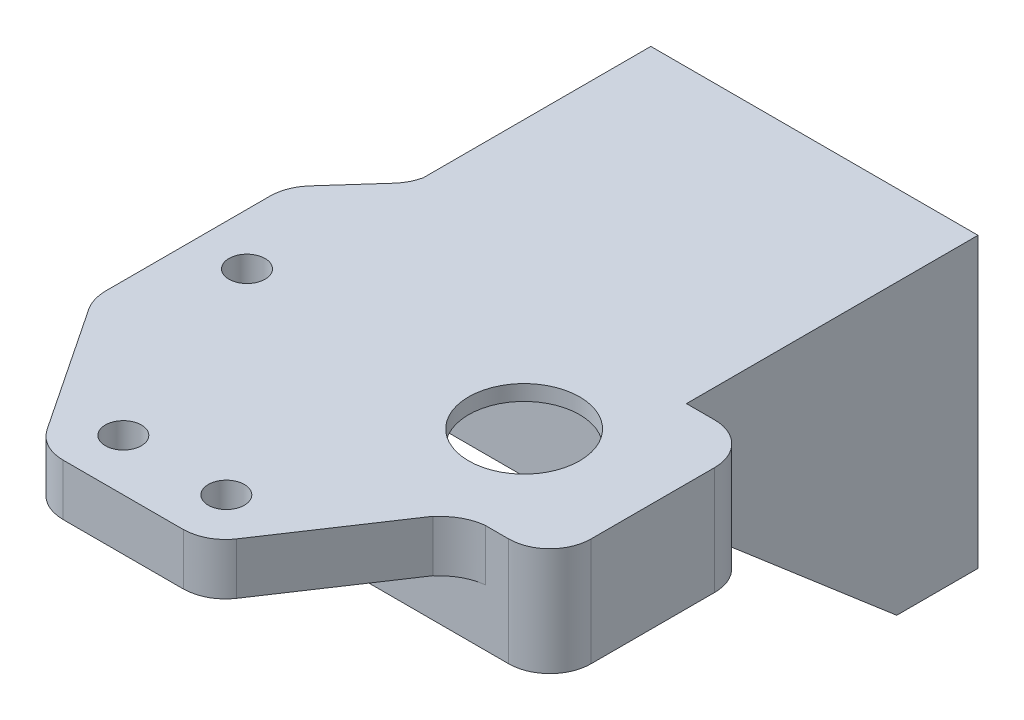
SolidWorks part; units mm, degrees
ref_plane "Alzado" through (0, 0, 0) normal (0, 0, 1) x (1, 0, 0)
ref_plane "Planta" through (0, 0, 0) normal (0, 1, 0) x (1, 0, 0)
ref_plane "Vista lateral" through (0, 0, 0) normal (1, 0, 0) x (0, 0, -1)
sketch "Croquis2" plane through (0, 0, 0) normal (0, 1, 0) x (1, 0, 0)
  line L0 (-15.9202, -3.4567) -> (19.0798, -3.4567)
  line L1 (19.0798, -3.4567) -> (19.0798, 16.5433)
  line L2 (19.0798, 16.5433) -> (-15.9202, 16.5433)
  line L3 (-15.9202, 16.5433) -> (-15.9202, -3.4567)
  dimension "D1" = 35
  dimension "D2" = 20
extrude "Saliente-Extruir1" add sketch "Croquis2" along normal blind 10.5
sketch "Croquis3" plane through (0, 0, 0) normal (0, -1, 0) x (1, 0, 0)
  line L0 (-9.9202, -0.0433) -> (-9.9202, -13.0433)
  line L1 (-9.9202, -13.0433) -> (13.0798, -13.0433)
  line L2 (13.0798, -13.0433) -> (13.0798, -0.0433)
  line L3 (13.0798, -0.0433) -> (-9.9202, -0.0433)
  line L4 (-15.9202, 3.4567) -> (19.0798, 3.4567) construction
  line L5 (19.0798, 3.4567) -> (19.0798, -16.5433) construction
  point P8 (0, 0)
  dimension "D1" = 23
  dimension "D2" = 13
  dimension "D3" = 3.5
  dimension "D4" = 6
extrude "Cortar-Extruir1" cut sketch "Croquis3" against normal blind 9
sketch "Croquis4" plane through (0, 0, 0) normal (0, -1, 0) x (1, 0, 0)
  line L0 (-9.9202, -0.0433) -> (-9.9202, -13.0433) construction
  line L1 (-15.9202, 3.4567) -> (19.0798, 3.4567) construction
  line L2 (13.0798, -13.0433) -> (13.0798, -0.0433) construction
  circle A0 centre (-12.2202, -6.5433) radius 1
  circle A1 centre (15.3798, -6.5433) radius 1
  dimension "D1" = 2
  dimension "D4" = 2.3
  dimension "D2" = 2.3
  dimension "D3" = 10
  dimension "D5" = 10
extrude "Cortar-Extruir2" cut sketch "Croquis4" against normal blind 4
sketch "Croquis5" plane through (0, 9, 0) normal (0, -1, 0) x (1, 0, 0)
  line L0 (13.0798, -0.0433) -> (-9.9202, -0.0433) construction
  line L1 (-9.9202, -0.0433) -> (-9.9202, -13.0433) construction
  circle A0 centre (6.5798, -6.5433) radius 5.386
  dimension "D1" = 10.772
  dimension "D2" = 6.5
  dimension "D3" = 16.5
extrude "Cortar-Extruir3" cut sketch "Croquis5" against normal blind 4
fillet "Redondeo1" radius 4 4 edges at (19.0798, 5.25, 3.4567) (-15.9202, 5.25, 3.4567) (-15.9202, 5.25, -16.5433) (19.0798, 5.25, -16.5433)
sketch "Croquis9" plane through (0, 10.5, 0) normal (0, 1, 0) x (1, 0, 0)
  line L0 (15.0798, 16.5433) -> (12.3366, 16.5433)
  line L1 (15.0798, 16.5433) -> (-11.9202, 16.5433) construction
  line L2 (1.8526, 25.3713) -> (9.5086, 17.7143)
  line L3 (-0.9754, 26.5433) -> (-19.3184, 26.5433)
  line L4 (-19.3184, 26.5433) -> (-19.3184, 23.5993)
  line L5 (13.0798, 0.0433) -> (-9.9202, 0.0433) construction
  line L6 (-20.3382, 20.9333) -> (-24.3012, 16.5023)
  line L7 (-25.3202, 13.8353) -> (-25.3202, -2.2447)
  line L8 (-24.6492, -4.4627) -> (-16.5092, -16.6747)
  line L9 (-13.1822, -18.4567) -> (-1.4642, -18.4567)
  line L10 (9.4928, -5.2377) -> (1.8628, -16.6747)
  line L11 (12.8208, -3.4567) -> (15.0798, -3.4567)
  line L12 (19.0798, 12.5433) -> (19.0798, 0.5433)
  arc A0 (19.0798, 12.5433) -> (15.0798, 16.5433) centre (15.0798, 12.5433) ccw construction
  arc A1 (15.0798, -3.4567) -> (19.0798, 0.5433) centre (15.0798, 0.5433) ccw construction
  spline S0 degree 2 poles (12.3366, 16.5433) (10.6986, 16.5878) (9.5086, 17.7143) knots 0 0 0 1 1 1
  spline S1 degree 2 poles (1.8526, 25.3713) (0.6624, 26.4974) (-0.9754, 26.5433) knots 0 0 0 1 1 1
  spline S2 degree 2 poles (-19.3184, 23.5993) (-19.3581, 22.0864) (-20.3382, 20.9333) knots 0 0 0 1 1 1
  spline S3 degree 2 poles (-24.3012, 16.5023) (-25.2821, 15.3489) (-25.3202, 13.8353) knots 0 0 0 1 1 1
  spline S4 degree 2 poles (-25.3202, -2.2447) (-25.2872, -3.4567) (-24.6492, -4.4627) knots 0 0 0 1 1 1
  spline S5 degree 2 poles (-16.5092, -16.6747) (-15.2925, -18.3998) (-13.1822, -18.4567) knots 0 0 0 1 1 1
  spline S6 degree 2 poles (-1.4642, -18.4567) (0.6651, -18.358) (1.8628, -16.6747) knots 0 0 0 1 1 1
  spline S7 degree 2 poles (9.4928, -5.2377) (10.9831, -3.6364) (12.8208, -3.4567) knots 0 0 0 0.396538 0.396538 0.396538
  spline S8 degree 2 poles (15.0798, -3.4567) (18.7366, -3.1135) (19.0798, 0.5433) knots 0 0 0 1 1 1
  spline S9 degree 2 poles (15.0798, 16.5433) (18.7366, 16.2002) (19.0798, 12.5433) knots 0 0 0 1 1 1
  point P5 (10.8106, 16.8583)
  point P6 (9.5086, 17.7143)
  point P9 (1.8526, 25.3713)
  point P12 (0.5506, 26.2273)
  point P13 (-0.9754, 26.5433)
  point P15 (-19.5932, 22.1763)
  point P19 (-20.3382, 20.9333)
  point P22 (-24.3012, 16.5023)
  point P25 (-25.0462, 15.2593)
  point P26 (-25.3202, 13.8353)
  point P30 (-25.0432, -3.6777)
  point P31 (-24.6492, -4.4627)
  point P33 (-16.5092, -16.6747)
  point P38 (-15.0692, -17.9827)
  point P40 (-13.1822, -18.4567)
  point P42 (0.6978, -17.8057)
  point P45 (1.8628, -16.6747)
  point P47 (9.4928, -5.2377)
  point P50 (12.8208, -3.4567)
  point P58 (17.9082, 15.3717)
  point P59 (17.9082, -2.2851)
  dimension "D1" = 2.7431
  dimension "D2" = 1.526
  dimension "D3" = 3.815
  dimension "D4" = 1.302
  dimension "D5" = 4.671
  dimension "D6" = 7.656
  dimension "D7" = 12.328
  dimension "D8" = 1.302
  dimension "D9" = 13.184
  dimension "D10" = 1.526
  dimension "D11" = 13.5
  dimension "D12" = 18.343
  dimension "D13" = 2.944
  dimension "D14" = 4.367
  dimension "D15" = 9.673
  dimension "D16" = 5.61
  dimension "D17" = 10.418
  dimension "D18" = 10.041
  dimension "D19" = 14.381
  dimension "D20" = 11.284
  dimension "D21" = 15.126
  dimension "D22" = 15.4
  dimension "D23" = 12.708
  dimension "D24" = 16.08
  dimension "D25" = 0.277
  dimension "D26" = 0.394
  dimension "D27" = 1.433
  dimension "D28" = 0.785
  dimension "D29" = 8.14
  dimension "D30" = 16.718
  dimension "D31" = 1.44
  dimension "D32" = 18.026
  dimension "D33" = 1.887
  dimension "D34" = 18.5
  dimension "D35" = 11.718
  dimension "D36" = 2.162
  dimension "D37" = 17.849
  dimension "D38" = 1.165
  dimension "D39" = 16.718
  dimension "D40" = 5.281
  dimension "D41" = 3.587
  dimension "D42" = 3.328
  dimension "D43" = 3.5
  dimension "D44" = 2.259
extrude "Saliente-Extruir2" add sketch "Croquis9" against normal blind 5
sketch "Croquis13" plane through (0, 0, 0) normal (0, -1, 0) x (1, 0, 0)
  line L0 (-9.9202, -0.0433) -> (-9.9202, -13.0433)
  line L1 (-9.9202, -13.0433) -> (13.0798, -13.0433)
  line L2 (13.0798, -13.0433) -> (13.0798, -0.0433)
  line L3 (13.0798, -0.0433) -> (-9.9202, -0.0433)
extrude "Cortar-Extruir4" cut sketch "Croquis13" against normal blind 9
sketch "Croquis14" plane through (0, 9, 0) normal (0, -1, 0) x (1, 0, 0)
  line L0 (13.0798, -0.0433) -> (-9.9202, -0.0433) construction
  line L1 (-9.9202, -0.0433) -> (-9.9202, -13.0433) construction
  circle A0 centre (6.5798, -6.5433) radius 5.386
  dimension "D3" = 10.772
  dimension "D1" = 6.5
  dimension "D2" = 16.5
extrude "Cortar-Extruir5" cut sketch "Croquis14" against normal up to next
sketch "Croquis15" plane through (0, 10.5, 0) normal (0, 1, 0) x (1, 0, 0)
  line L0 (-9.9202, 0.0433) -> (-9.9202, 13.0433) construction
  line L1 (13.0798, 0.0433) -> (-9.9202, 0.0433) construction
  line L2 (-24.6492, -4.4627) -> (-16.5092, -16.6747) construction
  line L3 (1.8628, -16.6747) -> (9.4928, -5.2377) construction
  circle A0 centre (-20.3202, 6.5443) radius 1.75
  circle A1 centre (-12.3243, -13.4532) radius 1.75
  circle A2 centre (-2.3243, -13.4567) radius 1.75
  dimension "D1" = 3.5
  dimension "D4" = 3.5
  dimension "D2" = 10.4
  dimension "D3" = 7.291
  dimension "D5" = 10
  dimension "D6" = 13.5
  dimension "D7" = 5.269
  dimension "D8" = 5.269
extrude "Cortar-Extruir6" cut sketch "Croquis15" against normal up to next
sketch "Croquis16" plane through (0, 10.5, 0) normal (0, 1, 0) x (1, 0, 0)
  line L0 (-19.3184, 26.5433) -> (-19.3184, 44.8418)
  line L1 (-19.3184, 44.8418) -> (12.3366, 44.8418)
  line L2 (12.3366, 16.5433) -> (12.3366, 44.8418)
  line L3 (-19.3184, 26.5433) -> (-0.9754, 26.5433)
  line L4 (1.8526, 25.3713) -> (9.5086, 17.7143)
  parabola Q0 (12.3366, 16.5433) -> (9.5086, 17.7143) focus (11.5758, 18.7062) apex (10.8106, 16.8583) construction
  parabola Q1 (1.8526, 25.3713) -> (-0.9754, 26.5433) focus (-0.2166, 24.3763) apex (0.5506, 26.2273) construction
  spline S0 degree 2 poles (9.5086, 17.7143) (10.6986, 16.5878) (12.3366, 16.5433) knots 0 0 0 1 1 1
  spline S1 degree 2 poles (-0.9754, 26.5433) (0.6624, 26.4974) (1.8526, 25.3713) knots 0 0 0 1 1 1
sketch "Croquis17" plane through (19.0798, 0, 0) normal (1, 0, 0) x (0, 0, -1)
  line L0 (44.8418, 10.5) -> (44.8418, -17.5)
  line L1 (16.5433, 10.5) -> (44.8418, 10.5) construction
  line L2 (44.8418, -17.5) -> (16.5433, -17.5)
  line L3 (16.5433, -17.5) -> (16.5433, 10.5)
  line L4 (16.5433, 10.5) -> (44.8418, 10.5)
  dimension "D1" = 28
extrude "Saliente-Extruir5" add sketch "Croquis17" against normal blind 38.5
sketch "Croquis18" plane through (0, 10.5, 0) normal (0, 1, 0) x (1, 0, 0)
  line L0 (12.3366, 16.5433) -> (19.0798, 16.5433)
  line L1 (19.0798, 16.5433) -> (19.0798, 44.8418)
  line L2 (19.0798, 44.8418) -> (12.3366, 44.8418)
  line L3 (12.3366, 44.8418) -> (12.3366, 16.5433)
extrude "Cortar-Extruir7" cut sketch "Croquis18" against normal blind 38.5
sketch "Croquis19" plane through (0, 0, -16.5433) normal (0, 0, 1) x (1, 0, 0)
  line L0 (-16.4202, -17.5) -> (9.3366, -17.5)
  line L1 (-19.4202, -17.5) -> (12.3366, -17.5) construction
  line L2 (9.3366, -17.5) -> (9.3366, 2.5)
  line L3 (9.3366, 2.5) -> (-16.4202, 2.5)
  line L4 (-16.4202, 2.5) -> (-16.4202, -17.5)
  line L5 (-19.4202, 5.5) -> (-19.4202, -17.5) construction
  line L6 (12.3366, -17.5) -> (12.3366, 0) construction
  line L7 (-19.4202, 5.5) -> (-11.9202, 5.5) construction
  dimension "D1" = 3
  dimension "D2" = 3
  dimension "D3" = 3
extrude "Cortar-Extruir8" cut sketch "Croquis19" against normal blind 20.5
sketch "Croquis20" plane through (0, 0, -37.0433) normal (0, 0, 1) x (1, 0, 0)
  line L0 (-16.4202, -17.5) -> (9.3366, -17.5) construction
  line L1 (-13.1822, 5.5) -> (-1.4642, 5.5) construction
  line L2 (-19.4202, 5.5) -> (-19.4202, -17.5) construction
  line L3 (-7.0418, -2.5) -> (-0.0418, -2.5)
  line L5 (-0.0418, -9.5) -> (-7.0418, -9.5)
  arc A0 (-7.0418, -2.5) -> (-7.0418, -9.5) centre (-7.0418, -6) ccw
  arc A1 (-0.0418, -2.5) -> (-0.0418, -9.5) centre (-0.0418, -6) cw
  point P0 (-3.5418, -17.5)
  point P1 (-3.5418, 5.5)
  point P4 (-19.4202, -6)
  point P7 (-3.5418, -6)
  dimension "D1" = 7
  dimension "D2" = 7
  dimension "D3" = 3.5
extrude "Cortar-Extruir9" cut sketch "Croquis20" against normal blind 3
sketch "Croquis21" plane through (0, 0, -40.0433) normal (0, 0, 1) x (1, 0, 0)
  circle A0 centre (-3.5418, -6) radius 2.49
  circle A3 centre (-8.0418, -6) radius 1.3
  circle A4 centre (0.9582, -6) radius 1.3
  dimension "D1" = 4.98
  dimension "D2" = 2.6
  dimension "D3" = 2.6
  dimension "D4" = 4.5
  dimension "D5" = 4.5
extrude "Cortar-Extruir10" cut sketch "Croquis21" against normal blind 5
sketch "Croquis22" plane through (12.3366, 0, 0) normal (1, 0, 0) x (0, 0, -1)
  line L1 (16.5433, -17.5) -> (44.8418, -17.5) construction
  line L2 (16.5433, 0) -> (36.9544, -17.5)
  line L3 (16.5433, 0) -> (16.5433, -17.5)
  line L4 (16.5433, -17.5) -> (36.9544, -17.5)
extrude "Cortar-Extruir11" cut sketch "Croquis22" against normal blind 32
